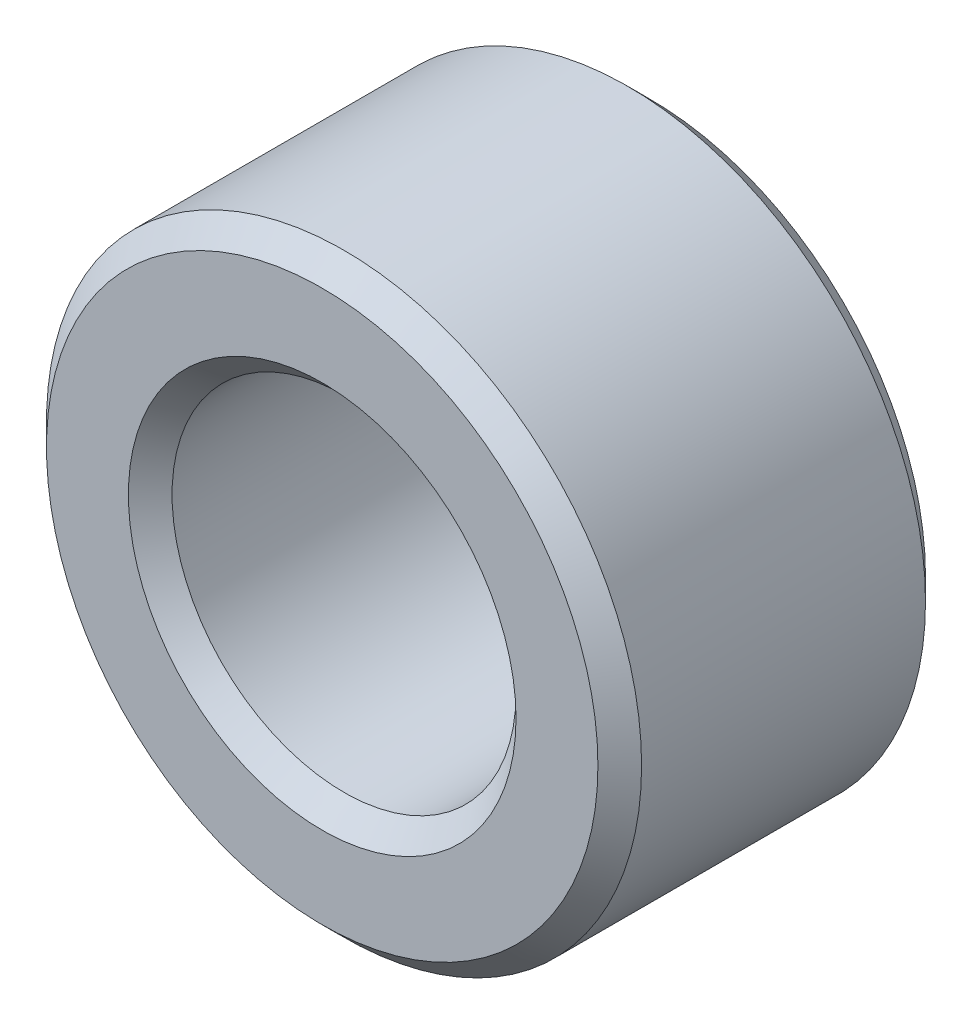
SolidWorks part; units mm, degrees
ref_plane "Front" through (0, 0, 0) normal (0, 0, 1) x (1, 0, 0)
ref_plane "Top" through (0, 0, 0) normal (0, 1, 0) x (1, 0, 0)
ref_plane "Right" through (0, 0, 0) normal (1, 0, 0) x (0, 0, -1)
sketch "Sketch1" plane through (0, 0, 0) normal (0, 0, 1) x (1, 0, 0)
  circle A0 centre (0, 0) radius 1.575
  circle A1 centre (0, 0) radius 2.725
  dimension "D1" = 3.15
  dimension "D2" = 5.45
extrude "Boss-Extrude1" add sketch "Sketch1" along normal blind 3
chamfer "Deburs" distance 0.2 angle 45 4 edges at (1.575, 0, 0) (1.575, 0, 3) (2.725, 0, 0) (2.725, 0, 3)
equation "\"D1@Sketch1\"=\"Hardware Clearance Hole Diameter@Box Assy.Assembly\""
equation "\"D2@Sketch1\"=\"Hardware Head Countersink Diameter@Box Assy.Assembly\"-.15mm"
